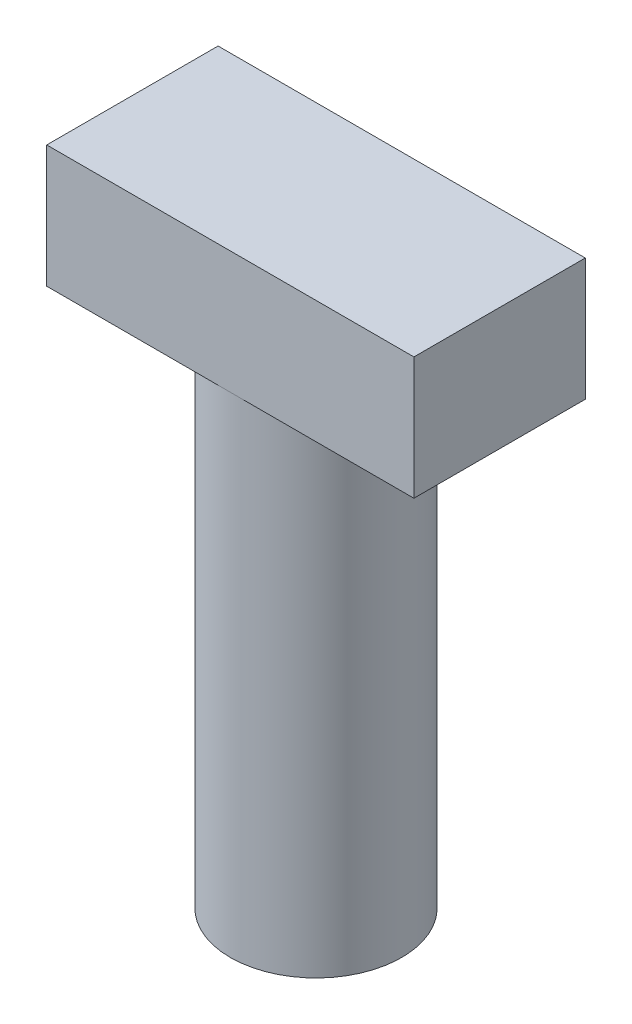
SolidWorks part; units mm, degrees
ref_plane "Front Plane" through (0, 0, 0) normal (0, 0, 1) x (1, 0, 0)
ref_plane "Top Plane" through (0, 0, 0) normal (0, 1, 0) x (1, 0, 0)
ref_plane "Right Plane" through (0, 0, 0) normal (1, 0, 0) x (0, 0, -1)
sketch "Sketch1" plane through (0, 0, 0) normal (0, 1, 0) x (1, 0, 0)
  circle A0 centre (0, 0) radius 7
  dimension "D1" = 14
extrude "Boss-Extrude1" add sketch "Sketch1" along normal blind 40
sketch "Sketch2" plane through (0, 40, 0) normal (0, 1, 0) x (1, 0, 0)
  line L1 (-15, 7) -> (15, 7)
  line L2 (-15, 7) -> (-15, -7)
  line L3 (-15, -7) -> (15, -7)
  line L4 (15, 7) -> (15, -7)
  dimension "D1" = 14
  dimension "D2" = 30
  dimension "D3" = 7
  dimension "D4" = 15
extrude "Boss-Extrude2" add sketch "Sketch2" along normal blind 10
